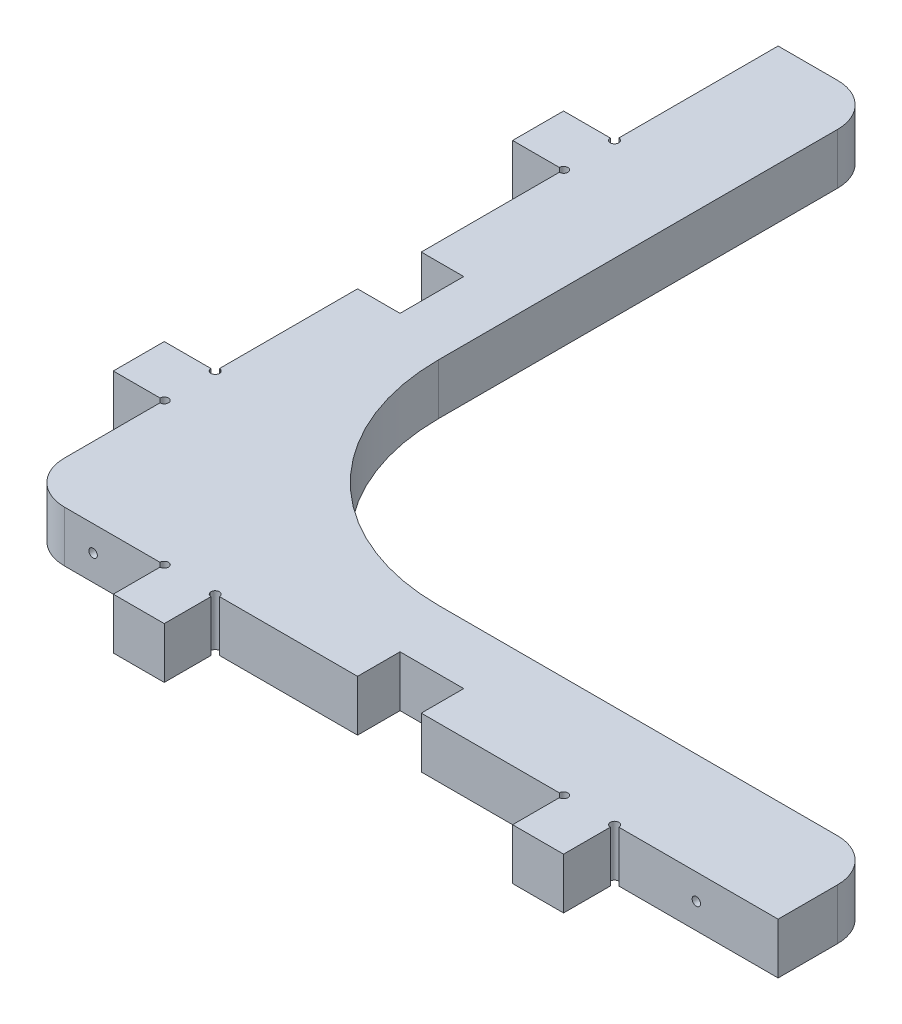
SolidWorks part; units mm, degrees
ref_plane "Front Plane" through (0, 0, 0) normal (0, 0, 1) x (1, 0, 0)
ref_plane "Top Plane" through (0, 0, 0) normal (0, 1, 0) x (1, 0, 0)
ref_plane "Right Plane" through (0, 0, 0) normal (1, 0, 0) x (0, 0, -1)
sketch "Sketch1" plane through (0, 0, 0) normal (0, 1, 0) x (1, 0, 0)
  line L0 (-5.5, 132.8438) -> (-5.5, 94.3438)
  line L1 (-5.5, 94.3438) -> (-17.5, 94.3438)
  line L2 (-17.5, 94.3438) -> (-17.5, 82.3438)
  line L3 (-17.5, 82.3438) -> (-5.5, 82.3438)
  line L4 (-5.5, 82.3438) -> (-5.5, 48.8438)
  line L5 (-5.5, 48.8438) -> (4.5, 48.8438)
  line L6 (4.5, 48.8438) -> (4.5, 33.8438)
  line L7 (4.5, 33.8438) -> (-5.5, 33.8438)
  line L8 (-5.5, 33.8438) -> (-5.5, 0.3438)
  line L9 (-5.5, 0.3438) -> (-17.5, 0.3438)
  line L10 (-17.5, 0.3438) -> (-17.5, -11.6562)
  line L11 (-17.5, -11.6562) -> (-5.5, -11.6562)
  line L12 (-5.5, -11.6562) -> (-5.5, -35.1562)
  line L13 (4.5, -45.1562) -> (28, -45.1562)
  line L14 (28, -45.1562) -> (28, -57.1562)
  line L15 (28, -57.1562) -> (40, -57.1562)
  line L16 (40, -57.1562) -> (40, -45.1562)
  line L17 (40, -45.1562) -> (73.5, -45.1562)
  line L18 (73.5, -45.1562) -> (73.5, -35.1562)
  line L19 (73.5, -35.1562) -> (88.5, -35.1562)
  line L20 (88.5, -35.1562) -> (88.5, -45.1562)
  line L21 (88.5, -45.1562) -> (122, -45.1562)
  line L22 (122, -45.1562) -> (122, -57.1562)
  line L23 (122, -57.1562) -> (134, -57.1562)
  line L24 (134, -57.1562) -> (134, -45.1562)
  line L25 (134, -45.1562) -> (172.5, -45.1562)
  line L26 (172.5, -45.1562) -> (172.5, -31.1562)
  line L27 (162.5, -21.1562) -> (68.5, -21.1562)
  line L28 (18.5, 28.8438) -> (18.5, 122.8438)
  line L29 (8.5, 132.8438) -> (-5.5, 132.8438)
  arc A0 (68.5, -21.1562) -> (18.5, 28.8438) centre (68.5, 28.8438) cw
  arc A1 (172.5, -31.1562) -> (162.5, -21.1562) centre (162.5, -31.1562) ccw
  arc A2 (18.5, 122.8438) -> (8.5, 132.8438) centre (8.5, 122.8438) ccw
  arc A3 (-5.5, -35.1562) -> (4.5, -45.1562) centre (4.5, -35.1563) ccw
  point P36 (18.5, 132.8438)
  point P39 (-5.5, -45.1562)
  dimension "D10" = 50
  dimension "D12" = 10
  dimension "D13" = 10
  dimension "D1" = 10
  dimension "D2" = 15
  dimension "D3" = 15
  dimension "D4" = 10
  dimension "D5" = 12
  dimension "D6" = 12
  dimension "D7" = 24
  dimension "D8" = 33.5
  dimension "D9" = 38.5
  dimension "D11" = 33.5
extrude "Boss-Extrude1" add sketch "Sketch1" along normal blind 12
sketch "Sketch2" plane through (0, 0, 45.1563) normal (0, 0, 1) x (1, 0, 0)
  line L0 (134, 12) -> (172.5, 12) construction
  line L1 (172.5, 12) -> (172.5, 0) construction
  line L2 (-5.5, 12) -> (-5.5, 0) construction
  line L3 (4.5, 12) -> (28, 12) construction
  circle A0 centre (153.25, 6) radius 0.9922
  circle A1 centre (11.25, 6) radius 0.9922
  dimension "D1" = 1.9844
  dimension "D2" = 1.9844
  dimension "D3" = 6
  dimension "D4" = 19.25
  dimension "D5" = 16.75
  dimension "D6" = 6
extrude "Cut-Extrude1" cut sketch "Sketch2" against normal blind 12
sketch "Sketch3" plane through (-5.5, 0, 0) normal (-1, 0, 0) x (0, 0, 1)
  line L0 (45.1562, 12) -> (45.1562, 0) construction
  line L1 (-132.8438, 12) -> (-132.8438, 0) construction
  line L2 (-132.8438, 12) -> (-94.3438, 12) construction
  line L3 (11.6563, 12) -> (35.1562, 12) construction
  circle A0 centre (28.4062, 6) radius 0.9922
  circle A1 centre (-113.5938, 6) radius 0.9922
  dimension "D1" = 1.9844
  dimension "D2" = 1.9844
  dimension "D3" = 16.75
  dimension "D4" = 19.25
  dimension "D5" = 6
  dimension "D6" = 6
extrude "Cut-Extrude2" cut sketch "Sketch3" against normal blind 12
sketch "Sketch4" plane through (0, 0, 0) normal (0, 1, 0) x (1, 0, 0)
  circle A0 centre (-5.5, 94.3438) radius 1
  circle A1 centre (-5.5, 82.3438) radius 1
  circle A2 centre (-5.5, 0.3438) radius 1
  circle A3 centre (-5.5, -11.6562) radius 1
  circle A4 centre (28, -45.1562) radius 1
  circle A5 centre (40, -45.1562) radius 1
  circle A6 centre (122, -45.1562) radius 1
  circle A7 centre (134, -45.1562) radius 1
  dimension "D1" = 2
extrude "Cut-Extrude3" cut sketch "Sketch4" along normal through all
